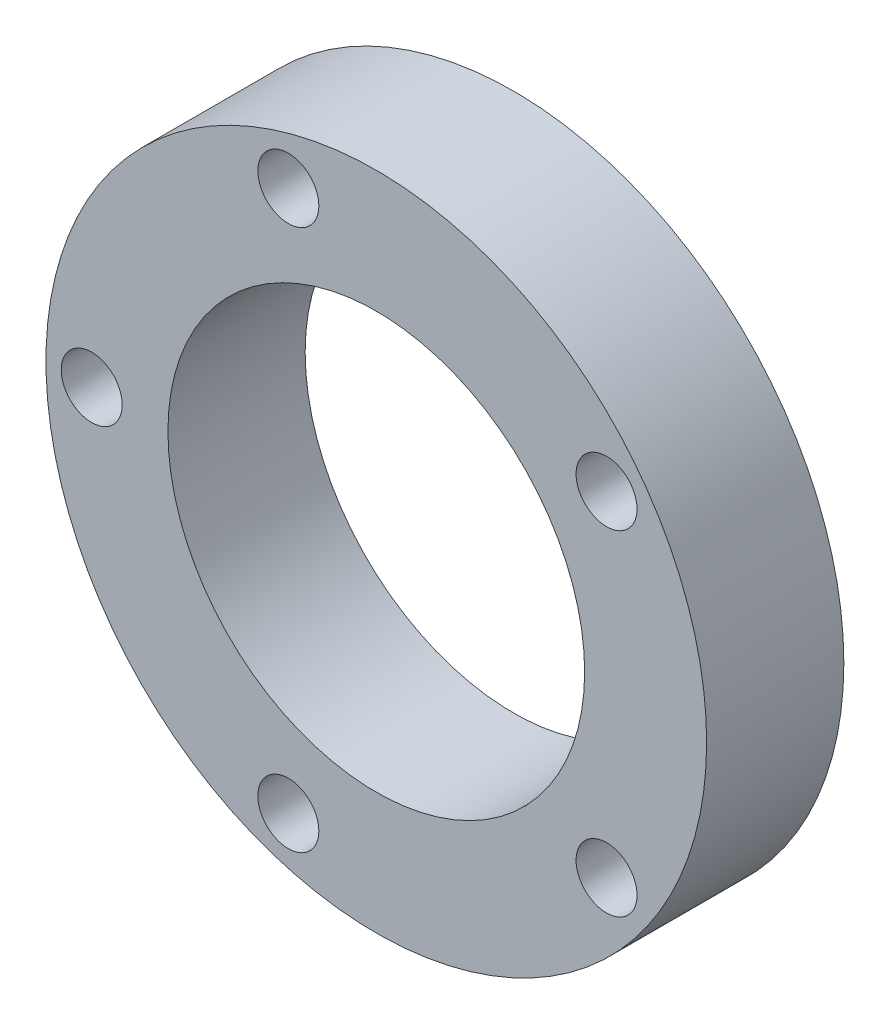
SolidWorks part; units mm, degrees
material "1.0553 (S355J0)"
ref_plane "Płaszczyzna przednia" through (0, 0, 0) normal (0, 0, 1) x (1, 0, 0)
ref_plane "Płaszczyzna górna" through (0, 0, 0) normal (0, 1, 0) x (1, 0, 0)
ref_plane "Płaszczyzna prawa" through (0, 0, 0) normal (1, 0, 0) x (0, 0, -1)
sketch "Szkic1" plane through (0, 0, 0) normal (0, 0, 1) x (1, 0, 0)
  circle A0 centre (0, 0) radius 65
  dimension "D1" = 130
extrude "Dodanie-wyciągnięcie1" add sketch "Szkic1" along normal blind 27
sketch "Szkic2" plane through (0, 0, 27) normal (0, 0, 1) x (1, 0, 0)
  circle A0 centre (-56, 0) radius 6
  circle A1 centre (-17.305, 53.2592) radius 6
  circle A2 centre (45.305, 32.916) radius 6
  circle A3 centre (45.305, -32.916) radius 6
  circle A4 centre (-17.305, -53.2592) radius 6
  circle A5 centre (0, 0) radius 41
  point P14 (0, 0)
  dimension "D1" = 12
  dimension "D4" = 82
  dimension "D2" = 56
  dimension "D3" = 5
extrude "Wytnij-wyciągnięcie1" cut sketch "Szkic2" against normal blind 35
